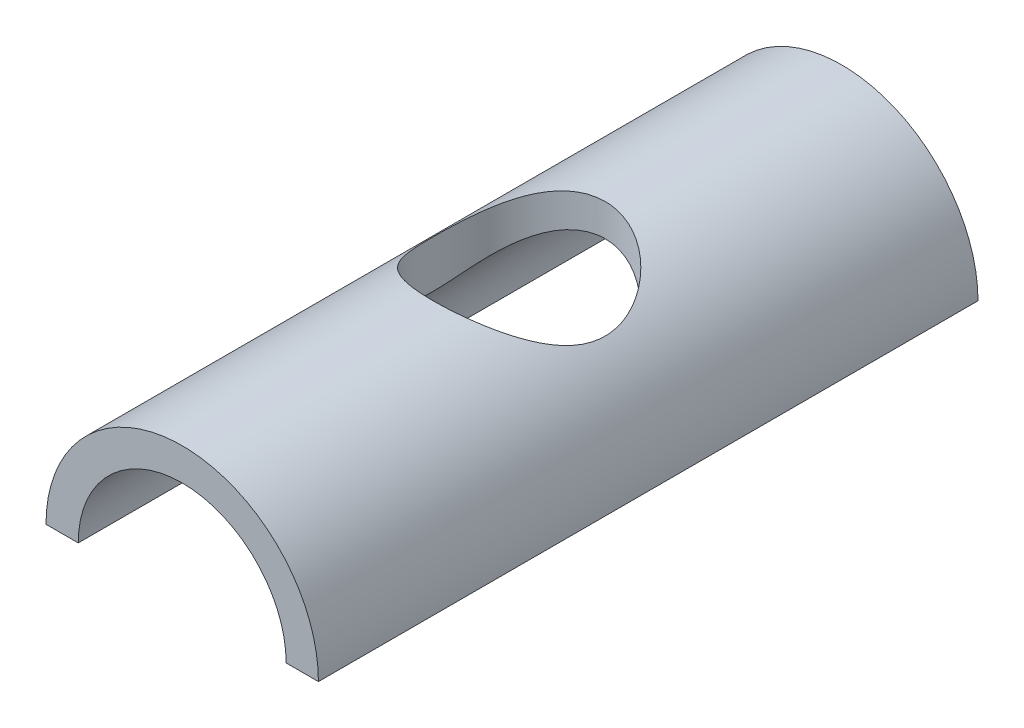
SolidWorks part; units mm, degrees
ref_plane "正面" through (0, 0, 0) normal (0, 0, 1) x (1, 0, 0)
ref_plane "平面" through (0, 0, 0) normal (0, 1, 0) x (1, 0, 0)
ref_plane "右側面" through (0, 0, 0) normal (1, 0, 0) x (0, 0, -1)
sketch "ｽｹｯﾁ1" plane through (0, 0, 0) normal (0, 0, 1) x (1, 0, 0)
  line L0 (-9.5, 0) -> (-7.25, 0)
  line L1 (7.25, 0) -> (9.5, 0)
  arc A0 (9.5, 0) -> (-9.5, 0) centre (0, 0) ccw
  arc A1 (7.25, 0) -> (-7.25, 0) centre (0, 0) ccw
  dimension "D1" = 14.5
  dimension "D2" = 19
extrude "ﾎﾞｽ - 押し出し1" add sketch "ｽｹｯﾁ1" along normal blind 46
sketch "ｽｹｯﾁ2" plane through (0, 0, 0) normal (0, 1, 0) x (1, 0, 0)
  line L0 (9.5, 0) -> (-9.5, 0) construction
  circle A0 centre (0, -22.5) radius 6
  dimension "D1" = 12
  dimension "D2" = 22.5
extrude "ｶｯﾄ - 押し出し1" cut sketch "ｽｹｯﾁ2" along normal blind 45
